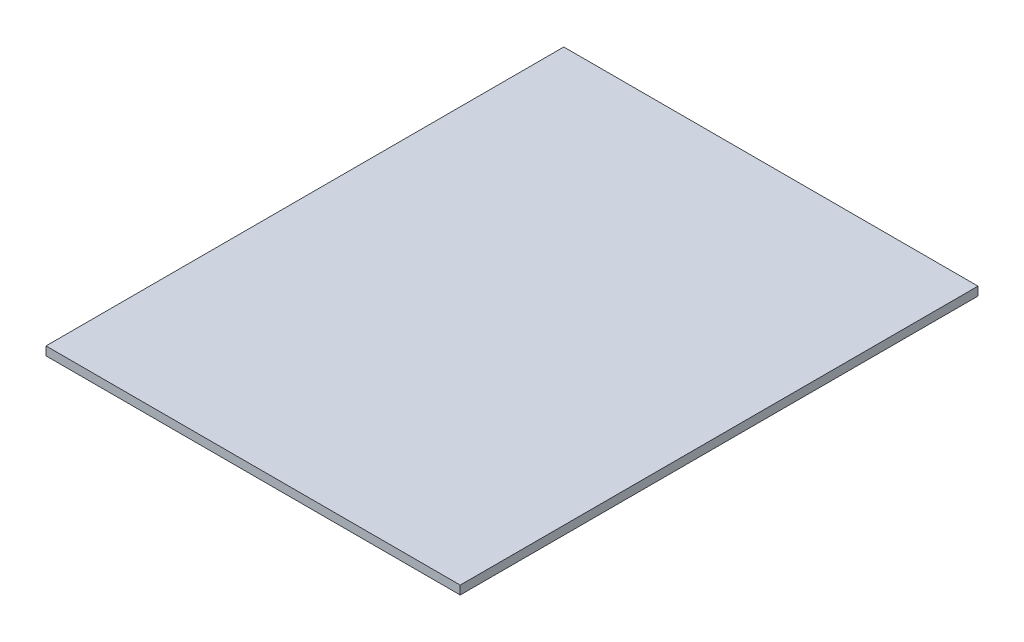
SolidWorks part; units mm, degrees
ref_plane "Front Plane" through (0, 0, 0) normal (0, 0, 1) x (1, 0, 0)
ref_plane "Top Plane" through (0, 0, 0) normal (0, 1, 0) x (1, 0, 0)
ref_plane "Right Plane" through (0, 0, 0) normal (1, 0, 0) x (0, 0, -1)
sketch "Sketch1" plane through (0, 0, 0) normal (0, 1, 0) x (1, 0, 0)
  line L1 (-150, -150) -> (154.8, -150)
  line L2 (-150, -150) -> (-150, 231)
  line L3 (-150, 231) -> (154.8, 231)
  line L4 (154.8, -150) -> (154.8, 231)
  point P0 (0, 0)
  dimension "D1" = 304.8
  dimension "D2" = 381
extrude "Boss-Extrude1" add sketch "Sketch1" along normal blind 6.35
